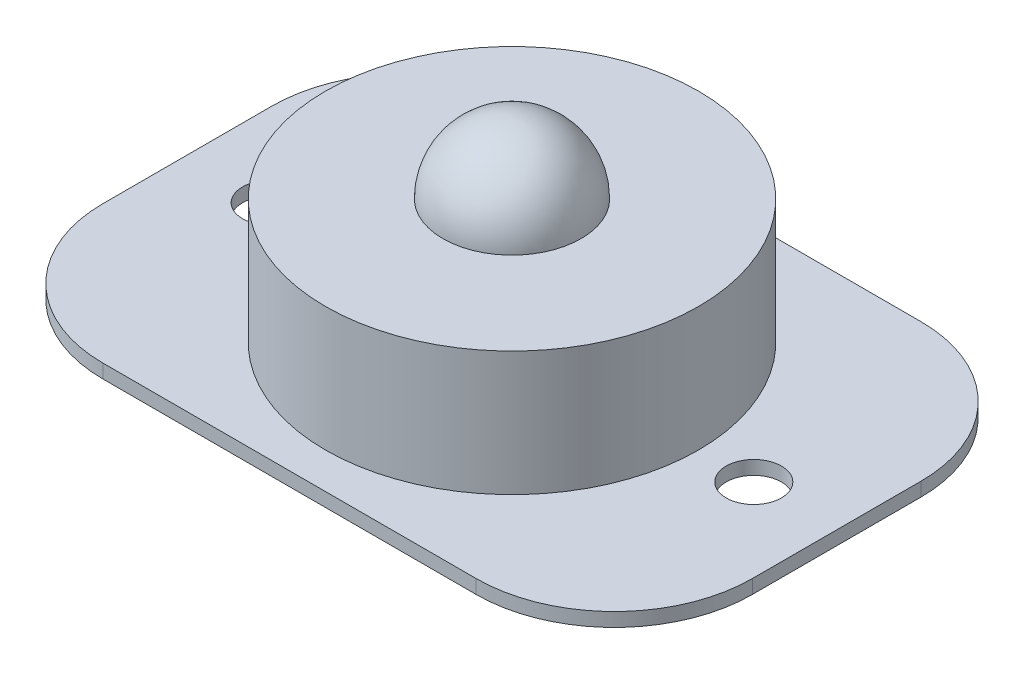
SolidWorks part; units mm, degrees
material "PBT 一般用途"
ref_plane "前视基准面" through (0, 0, 0) normal (0, 0, 1) x (1, 0, 0)
ref_plane "上视基准面" through (0, 0, 0) normal (0, 1, 0) x (1, 0, 0)
ref_plane "右视基准面" through (0, 0, 0) normal (1, 0, 0) x (0, 0, -1)
sketch "草图1" plane through (0, 0, 0) normal (0, 1, 0) x (1, 0, 0)
  line L1 (-23.5, -16.1) -> (23.5, -16.1)
  line L2 (-23.5, -16.1) -> (-23.5, 16.1)
  line L3 (-23.5, 16.1) -> (23.5, 16.1)
  line L4 (23.5, -16.1) -> (23.5, 16.1)
  line L5 (-23.5, -16.1) -> (23.5, 16.1) construction
  line L6 (-23.5, 16.1) -> (23.5, -16.1) construction
  circle A0 centre (0, 0) radius 16.1
  dimension "D1" = 32.2
  dimension "D2" = 32.2
  dimension "D3" = 47
extrude "凸台-拉伸1" add sketch "草图1" along normal blind 1 contours A0 L3 L2 L1 | A0 | A0 L1 L4 L3
sketch "草图2" plane through (0, 1, 0) normal (0, 1, 0) x (1, 0, 0)
  circle A0 centre (0, 0) radius 13.5
  dimension "D1" = 27
extrude "凸台-拉伸2" add sketch "草图2" along normal blind 9
ref_plane "基准面4" through (0, 0, 0) normal (-1, 0, 0) x (0, 0, 1)
sketch "草图3" plane through (0, 0, 0) normal (-1, 0, 0) x (0, 0, 1)
  line L0 (13.5, 10) -> (-13.5, 10) construction
  line L1 (0, 15) -> (0, 10)
  line L2 (0, 10) -> (5, 10)
  arc A0 (5, 10) -> (0, 15) centre (0, 10) ccw
  dimension "D1" = 10
ref_axis "基准轴1" through (0, 15, 0) along (0, -1, 0)
revolve "旋转1" add sketch "草图3" angle 360 about axis through (0, 15, 0) along (0, -1, 0)
sketch "草图4" plane through (0, 1, 0) normal (0, 1, 0) x (1, 0, 0)
  line L0 (0, 0) -> (17.5, 0)
  line L1 (0, 0) -> (-17.5, 0)
  dimension "D1" = 17.5
  dimension "D2" = 17.5
sketch "草图5" plane through (0, 1, 0) normal (0, 1, 0) x (1, 0, 0)
  point P0 (-17.5, 0)
  point P3 (17.5, 0)
hole_wizard "孔1" positions "草图5" profile "草图6" legacy end condition through all
sketch "草图6" plane through (-17.5, 1, 0) normal (1, 0, 0) x (0, 0, 1)
  line L0 (0, 0) -> (0, 1)
  line L1 (0, 1) -> (2, 1)
  line L2 (2, 1) -> (2, 0)
  line L3 (2, 0) -> (0, 0)
  line L4 (0, 110) -> (0, -10) construction
  dimension "直径" = 4
  dimension "深度" = 1
fillet "圆角1" radius 10 4 edges at (23.5, 0.5, -16.1) (23.5, 0.5, 16.1) (-23.5, 0.5, 16.1) (-23.5, 0.5, -16.1)
